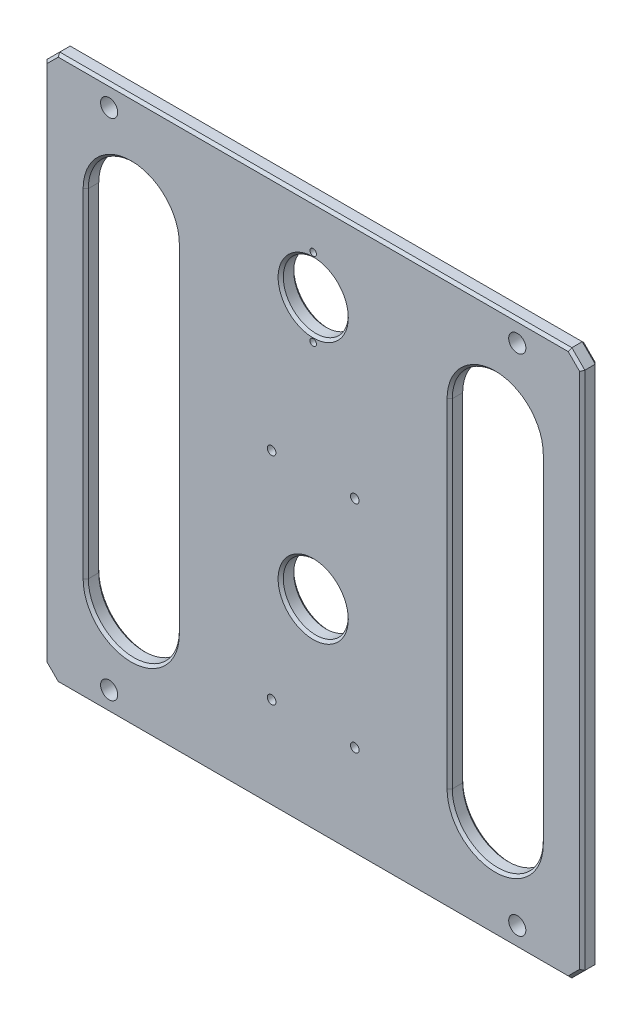
SolidWorks part; units mm, degrees
ref_plane "前视基准面" through (0, 0, 0) normal (0, 0, 1) x (1, 0, 0)
ref_plane "上视基准面" through (0, 0, 0) normal (0, 1, 0) x (1, 0, 0)
ref_plane "右视基准面" through (0, 0, 0) normal (1, 0, 0) x (0, 0, -1)
sketch "草图1" plane through (0, 0, 0) normal (0, 0, 1) x (1, 0, 0)
  line L1 (-103.5, 105) -> (103.5, 105)
  line L2 (-103.5, 105) -> (-103.5, -105)
  line L3 (-103.5, -105) -> (103.5, -105)
  line L4 (103.5, 105) -> (103.5, -105)
  line L5 (-103.5, 105) -> (103.5, -105) construction
  line L6 (-103.5, -105) -> (103.5, 105) construction
  point P0 (0, 0)
  dimension "D1" = 207
  dimension "D2" = 210
extrude "凸台-拉伸1" add sketch "草图1" along normal blind 6
sketch "草图2" plane through (0, 0, 6) normal (0, 0, 1) x (1, 0, 0)
  line L0 (103.5, 105) -> (-103.5, 105) construction
  line L1 (-78.5, -97) -> (78.5, -97) construction
  line L2 (-78.5, -97) -> (-78.5, 97) construction
  line L3 (-78.5, 97) -> (78.5, 97) construction
  line L4 (78.5, -97) -> (78.5, 97) construction
  line L5 (-78.5, -97) -> (78.5, 97) construction
  line L6 (-78.5, 97) -> (78.5, -97) construction
  line L7 (-103.5, 105) -> (-103.5, -105) construction
  circle A0 centre (-78.5, 97) radius 3.3
  circle A1 centre (78.5, 97) radius 3.3
  circle A2 centre (-78.5, -97) radius 3.3
  circle A3 centre (78.5, -97) radius 3.3
  point P0 (0, 0)
  dimension "D3" = 6.6
  dimension "D1" = 25
  dimension "D2" = 8
extrude "切除-拉伸1" cut sketch "草图2" against normal through all
chamfer "倒角2" distance 5 angle 45 4 edges at (-103.5, -105, 3) (103.5, -105, 3) (-103.5, 105, 3) (103.5, 105, 3)
chamfer "倒角1" distance 1 angle 45 16 edges at (-103.5, 0, 6) (-101, -102.5, 6) (-101, 102.5, 6) (0, -105, 6) (0, 105, 6) (101, -102.5, 6) (101, 102.5, 6) (103.5, 0, 6) (-103.5, 0, 0) (-101, -102.5, 0) (-101, 102.5, 0) (0, -105, 0) (0, 105, 0) (101, -102.5, 0) (101, 102.5, 0) (103.5, 0, 0)
hole_wizard "M4 螺纹孔1" positions "草图3" profile "草图4" tap size "M4" standard "GB"
sketch "草图3" plane through (0, 0, 0) normal (0, 0, -1) x (-1, 0, 0)
  point P0 (-16, 14)
  point P4 (16, 14)
  point P7 (16, -69)
  point P10 (-16, -69)
  point P13 (0, 0)
  point P14 (-16, 14)
  point P16 (0, 0)
  point P17 (16, 14)
  point P19 (0, 0)
  point P20 (16, -69)
  point P22 (0, 0)
  point P23 (-16, -69)
sketch "草图4" plane through (16, 14, 0) normal (1, 0, 0) x (0, 1, 0)
  line L0 (0, 0) -> (0, 11.0914)
  line L1 (0, 11.0914) -> (1.65, 10.1)
  line L2 (1.65, 10.1) -> (1.65, 0)
  line L5 (1.65, 0) -> (0, 0)
  line L10 (0, 11.0914) -> (-1.65, 10.1) construction
  line L11 (0, -6.35) -> (0, 107.95) construction
  dimension "螺纹孔钻头直径" = 3.3
  dimension "螺纹孔钻头深度" = 10.1
  dimension "导头角度" = 118
cosmetic thread "孔螺蚊线1" parameters "D1"=8, "D2"=4
cosmetic thread "孔螺蚊线2" parameters "D1"=8, "D2"=4
cosmetic thread "孔螺蚊线3" parameters "D1"=8, "D2"=4
cosmetic thread "孔螺蚊线4" parameters "D1"=8, "D2"=4
hole_wizard "M3 螺纹孔1" positions "草图5" profile "草图6" tap size "M3" standard "GB"
sketch "草图5" plane through (0, 0, 0) normal (0, 0, -1) x (-1, 0, 0)
  point P0 (0, 58)
  point P3 (0, 88)
sketch "草图6" plane through (0, 58, 0) normal (1, 0, 0) x (0, 1, 0)
  line L0 (0, 0) -> (0, 8.2511)
  line L1 (0, 8.2511) -> (1.25, 7.5)
  line L2 (1.25, 7.5) -> (1.25, 0)
  line L5 (1.25, 0) -> (0, 0)
  line L10 (0, 8.2511) -> (-1.25, 7.5) construction
  line L11 (0, -6.35) -> (0, 107.95) construction
  dimension "螺纹孔钻头直径" = 2.5
  dimension "螺纹孔钻头深度" = 7.5
  dimension "导头角度" = 118
cosmetic thread "孔螺蚊线5" parameters "D1"=6, "D2"=3
cosmetic thread "孔螺蚊线6" parameters "D1"=6, "D2"=3
sketch "草图7" plane through (0, 0, 0) normal (0, 0, -1) x (-1, 0, 0)
  line L0 (0, 88) -> (0, 58) construction
  circle A0 centre (0, 73) radius 12.5
  dimension "D1" = 25
extrude "切除-拉伸2" cut sketch "草图7" against normal through all
sketch "草图8" plane through (0, 0, 0) normal (0, 0, -1) x (-1, 0, 0)
  line L0 (-16, 14) -> (16, -69) construction
  circle A1 centre (0, -27.5) radius 12.5
  point P2 (-16.2233, 14)
  point P3 (-16, 14)
  point P7 (0, 0)
  dimension "D1" = 25
extrude "切除-拉伸3" cut sketch "草图8" against normal through all
sketch "草图9" plane through (0, 0, 0) normal (0, 0, -1) x (-1, 0, 0)
  line L0 (-70, 0) -> (70, 0) construction
  line L1 (-70, -65) -> (-70, 65) construction
  line L2 (-87.5, -65) -> (-87.5, 65)
  line L3 (-52.5, -65) -> (-52.5, 65)
  line L4 (70, -65) -> (70, 65) construction
  line L5 (52.5, -65) -> (52.5, 65)
  line L6 (87.5, -65) -> (87.5, 65)
  arc A0 (-87.5, -65) -> (-52.5, -65) centre (-70, -65) ccw
  arc A1 (-52.5, 65) -> (-87.5, 65) centre (-70, 65) ccw
  arc A2 (52.5, -65) -> (87.5, -65) centre (70, -65) ccw
  arc A3 (87.5, 65) -> (52.5, 65) centre (70, 65) ccw
  point P4 (0, 0)
  point P7 (-70, 0)
  point P13 (70, 0)
  dimension "D1" = 140
  dimension "D2" = 130
  dimension "D3" = 35
extrude "切除-拉伸4" cut sketch "草图9" against normal through all
chamfer "倒角3" distance 1 angle 45 20 edges at (-12.5, 73, 6) (-12.5, 73, 0) (-12.5, -27.5, 6) (-12.5, -27.5, 0) (70, -82.5, 6) (52.5, 0, 6) (87.5, 0, 6) (70, 82.5, 6) (70, -82.5, 0) (52.5, 0, 0) (87.5, 0, 0) (70, 82.5, 0) (-70, -82.5, 6) (-87.5, 0, 6) (-52.5, 0, 6) (-70, 82.5, 6) (-70, -82.5, 0) (-87.5, 0, 0) (-52.5, 0, 0) (-70, 82.5, 0)
